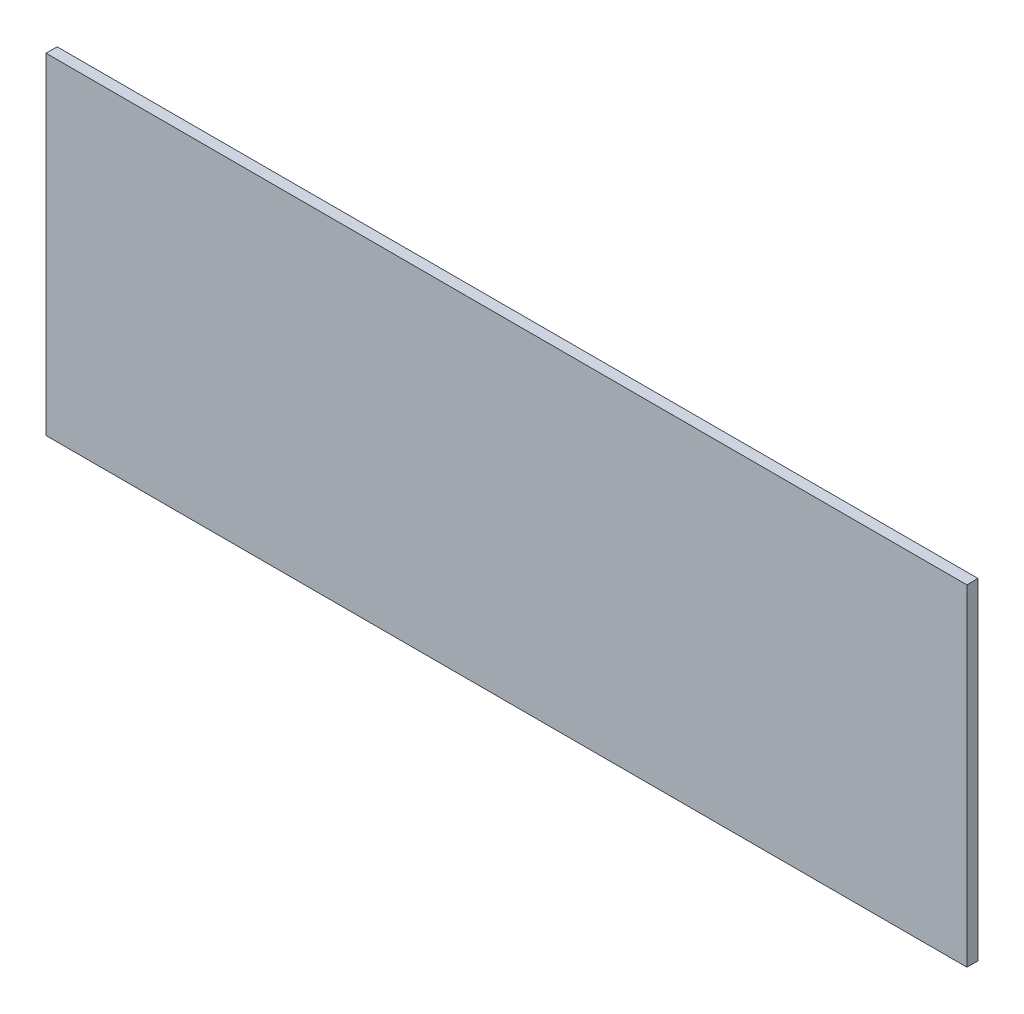
SolidWorks part; units mm, degrees
material "Acrylic (Medium-high impact)"
ref_plane "Front Plane" through (0, 0, 0) normal (0, 0, 1) x (1, 0, 0)
ref_plane "Top Plane" through (0, 0, 0) normal (0, 1, 0) x (1, 0, 0)
ref_plane "Right Plane" through (0, 0, 0) normal (1, 0, 0) x (0, 0, -1)
sketch "Sketch1" plane through (0, 0, 0) normal (0, 0, 1) x (1, 0, 0)
  line L1 (-231.775, 83.3437) -> (231.775, 83.3437)
  line L2 (-231.775, 83.3437) -> (-231.775, -83.3438)
  line L3 (-231.775, -83.3438) -> (231.775, -83.3438)
  line L4 (231.775, 83.3437) -> (231.775, -83.3438)
  line L5 (-231.775, 83.3437) -> (231.775, -83.3438) construction
  line L6 (-231.775, -83.3438) -> (231.775, 83.3437) construction
  point P0 (0, 0)
  dimension "D1" = 463.55
  dimension "D2" = 166.6875
extrude "Boss-Extrude1" add sketch "Sketch1" along normal blind 5.588
sketch "Sketch3" plane through (0, 83.3437, 0) normal (0, 1, 0) x (1, 0, 0)
  line L0 (231.775, 0) -> (-231.775, 0) construction
  line L1 (-231.775, -196.85) -> (231.775, -196.85)
  line L2 (-231.775, -196.85) -> (-231.775, 0)
  line L3 (-231.775, 0) -> (231.775, 0)
  line L4 (231.775, -196.85) -> (231.775, 0)
  line L5 (-231.775, -196.85) -> (231.775, 0) construction
  line L6 (-231.775, 0) -> (231.775, -196.85) construction
  point P0 (0, -98.425)
  dimension "D1" = 196.85
extrude "Boss-Extrude2" [suppressed] add sketch "Sketch3" along normal blind 5.588 separate body
sketch "Sketch5" [suppressed] plane through (231.775, 0, 0) normal (1, 0, 0) x (0, 0, -1)
  line L1 (-196.85, -83.3438) -> (-5.588, -83.3438)
  line L2 (-196.85, -83.3438) -> (-196.85, 83.3437)
  line L3 (-196.85, 83.3437) -> (-5.588, 83.3437)
  line L4 (-5.588, -83.3438) -> (-5.588, 83.3437)
  line L5 (-196.85, -83.3438) -> (-5.588, 83.3437) construction
  line L6 (-196.85, 83.3437) -> (-5.588, -83.3438) construction
  line L7 (-196.85, 88.9317) -> (-196.85, 83.3437) construction
  line L8 (-196.85, 83.3437) -> (0, 83.3437) construction
  line L9 (-5.588, -83.3438) -> (0, -83.3438) construction
  point P0 (-101.219, 0)
extrude "Boss-Extrude3" [suppressed] add sketch "Sketch5" against normal blind 5.588 separate body
sketch "Sketch6" [suppressed] plane through (-231.775, 0, 0) normal (-1, 0, 0) x (0, 0, 1)
  line L0 (196.85, -83.3437) -> (5.588, -83.3437) construction
  line L1 (196.85, -83.3437) -> (5.588, -83.3437)
  line L2 (196.85, -83.3437) -> (196.85, 83.3438)
  line L3 (196.85, 83.3438) -> (5.588, 83.3438)
  line L4 (5.588, -83.3437) -> (5.588, 83.3438)
  line L5 (196.85, -83.3437) -> (5.588, 83.3438) construction
  line L6 (196.85, 83.3438) -> (5.588, -83.3437) construction
  point P0 (101.219, 0)
extrude "Boss-Extrude4" [suppressed] add sketch "Sketch6" against normal blind 4.7625 separate body
sketch "Sketch7" [suppressed] plane through (0, 0, 4.7625) normal (0, 0, -1) x (-1, 0, 0)
  line L1 (-242.0938, -101.854) -> (-235.7438, -101.854)
  line L2 (-242.0938, -101.854) -> (-242.0938, -95.504)
  line L3 (-242.0938, -95.504) -> (-235.7438, -95.504)
  line L4 (-235.7438, -101.854) -> (-235.7438, -95.504)
  line L6 (-236.5375, -101.6) -> (-241.3, -101.6) construction
  line L7 (-238.9188, -101.854) -> (-238.9188, -101.6) construction
  line L8 (0, 0) -> (0, -111.4304) construction
  line L9 (238.9188, -101.854) -> (238.9188, -101.6) construction
  line L10 (235.7438, -101.854) -> (235.7438, -95.504)
  line L11 (242.0938, -95.504) -> (235.7438, -95.504)
  line L12 (242.0938, -101.854) -> (242.0938, -95.504)
  line L13 (242.0938, -101.854) -> (235.7438, -101.854)
  dimension "D1" = 0.254
  dimension "D2" = 6.35
  dimension "D3" = 6.35
extrude "Boss-Extrude5" [suppressed] add sketch "Sketch7" against normal up to surface (160.3375 mm away)
sketch "Sketch8" [suppressed] plane through (-231.775, 0, 0) normal (-1, 0, 0) x (0, 0, 1)
  line L1 (5.588, -83.3437) -> (196.85, -83.3437)
  line L2 (5.588, -83.3437) -> (5.588, 83.3437)
  line L3 (5.588, 83.3437) -> (196.85, 83.3437)
  line L4 (196.85, -83.3437) -> (196.85, 83.3437)
extrude "Boss-Extrude6" [suppressed] add sketch "Sketch8" against normal blind 5.588 separate body
